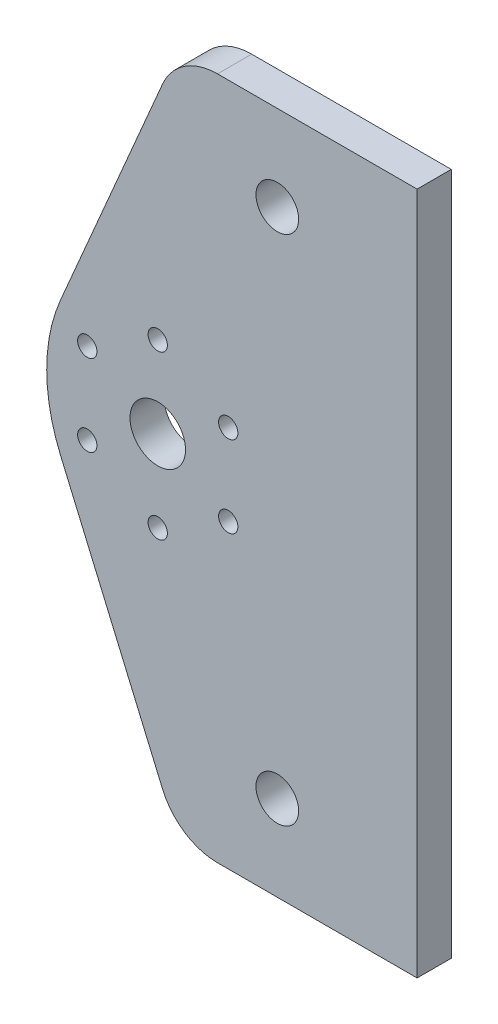
SolidWorks part; units mm, degrees
material "ABS"
ref_plane "Front Plane" through (0, 0, 0) normal (0, 0, 1) x (1, 0, 0)
ref_plane "Top Plane" through (0, 0, 0) normal (0, 1, 0) x (1, 0, 0)
ref_plane "Right Plane" through (0, 0, 0) normal (1, 0, 0) x (0, 0, -1)
sketch "Sketch1" plane through (0, 0, 0) normal (0, 0, 1) x (1, 0, 0)
  line L0 (0, -40) -> (0, 40)
  line L1 (-41.7527, -7.8788) -> (-29.804, -35.7576)
  line L3 (-23.37, -40) -> (0, -40)
  line L4 (-16.37, 30) -> (-16.37, 40) construction
  line L5 (-16.37, -30) -> (-16.37, -40) construction
  line L6 (-29.804, 35.7576) -> (-41.7527, 7.8788)
  line L8 (-23.37, 40) -> (0, 40)
  arc A0 (-41.7527, -7.8788) -> (-41.7527, 7.8788) centre (-23.37, 0) cw
  circle A1 centre (-30.37, 0) radius 9.53 construction
  circle A2 centre (-16.37, 30) radius 2.5
  circle A3 centre (-16.37, -30) radius 2.5
  circle A4 centre (-30.37, 0) radius 3.25
  arc A5 (-29.804, -35.7576) -> (-23.37, -40) centre (-23.37, -33) ccw
  arc A11 (-29.804, 35.7576) -> (-23.37, 40) centre (-23.37, 33) cw
  point P0 (-30.37, 0)
  point P11 (0, 0)
  dimension "D6" = 20
  dimension "D8" = 5
  dimension "D9" = 23.37
  dimension "D13" = 7
  dimension "D3" = 30.37
  dimension "D4" = 6.5
  dimension "D2" = 19.06
  dimension "D7" = 80
  dimension "D11" = 10
  dimension "D12" = 16.37
  dimension "D14" = 23.37
extrude "Boss-Extrude1" add sketch "Sketch1" along normal mid plane 4
hole_wizard "Taladro roscado #4-401" positions "Croquis2" profile "Croquis1" tap size "#4-40" standard "Ansi Inch"
sketch "Croquis2" plane through (0, 0, 2) normal (0, 0, 1) x (1, 0, 0)
  circle A0 centre (-30.37, 0) radius 9.53 construction
  point P0 (-30.37, -9.53)
  point P10 (-38.6232, -4.765)
  point P11 (-38.6232, 4.765)
  point P12 (-30.37, 9.53)
  point P13 (-22.1168, 4.765)
  point P14 (-22.1168, -4.765)
  dimension "D1" = 6
sketch "Croquis1" plane through (-30.37, -9.53, 2) normal (1, 0, 0) x (0, -1, 0)
  line L0 (0, 0) -> (0, 13.3792)
  line L1 (0, 13.3792) -> (1.1303, 12.7)
  line L2 (1.1303, 12.7) -> (1.1303, 0)
  line L5 (1.1303, 0) -> (0, 0)
  line L10 (0, 13.3792) -> (-1.1303, 12.7) construction
  line L11 (0, -6.35) -> (0, 107.95) construction
  dimension "Diámetro de perforador para roscar" = 2.2606
  dimension "Profundidad de perforador para roscar" = 12.7
  dimension "Ángulo de perforador" = 118
cosmetic thread "Rosca de taladro1"
cosmetic thread "Rosca de taladro2"
cosmetic thread "Rosca de taladro3"
cosmetic thread "Rosca de taladro4"
cosmetic thread "Rosca de taladro5"
cosmetic thread "Rosca de taladro6"
